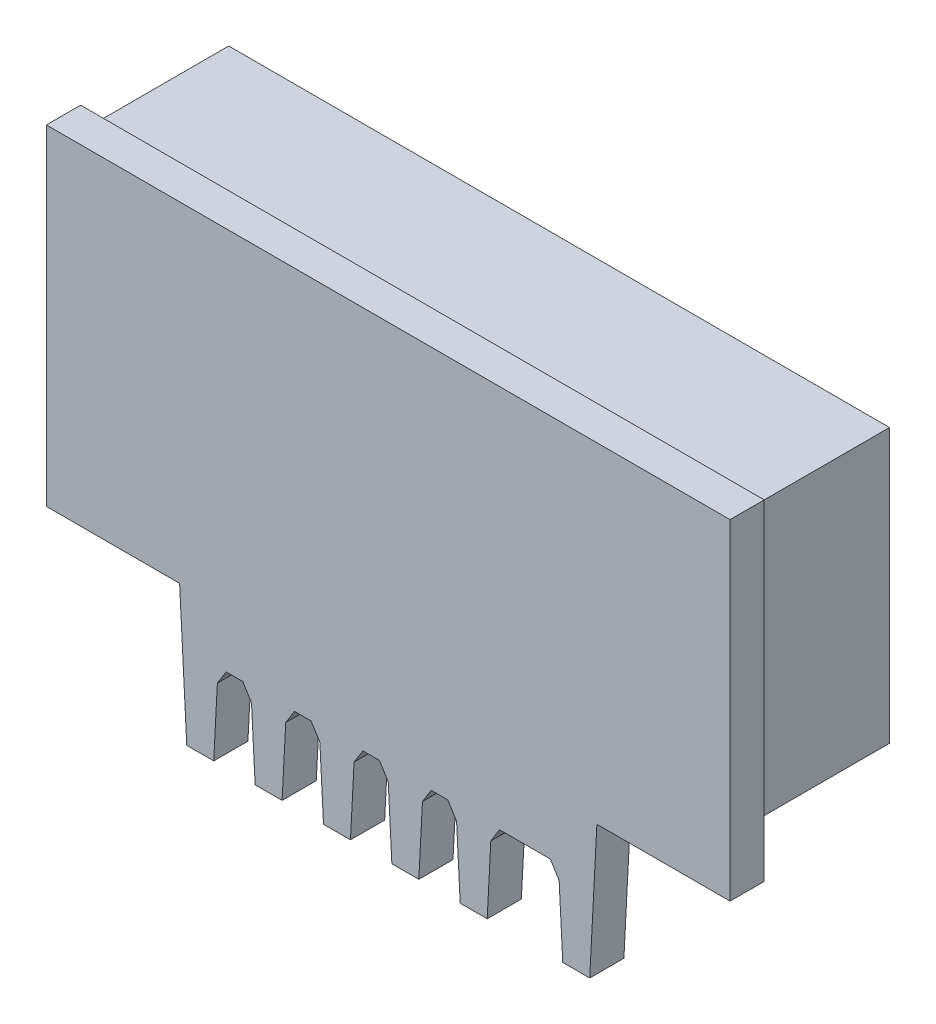
SolidWorks part; units mm, degrees
ref_plane "Front Plane" through (0, 0, 0) normal (0, 0, 1) x (1, 0, 0)
ref_plane "Top Plane" through (0, 0, 0) normal (0, 1, 0) x (1, 0, 0)
ref_plane "Right Plane" through (0, 0, 0) normal (1, 0, 0) x (0, 0, -1)
sketch "Sketch1" plane through (0, 0, 0) normal (0, 0, 1) x (1, 0, 0)
  line L0 (0, 0) -> (0, 20.5) construction
  line L1 (0, 20.5) -> (18.3124, 20.5) construction
  line L2 (18.3124, 20.5) -> (18.3124, 0) construction
  line L3 (18.3124, 0) -> (0, 0) construction
  line L4 (0, 3) -> (18.3124, 3) construction
  line L5 (0, 6) -> (18.3124, 6) construction
  line L6 (0.9062, 6) -> (0.9062, 0) construction
  line L7 (3.9062, 6) -> (3.9062, 0) construction
  line L8 (6.9062, 6) -> (6.9062, 0) construction
  line L9 (9.9062, 6) -> (9.9062, 0) construction
  line L10 (12.9062, 6) -> (12.9062, 0) construction
  line L11 (17.4062, 6) -> (17.4062, 0) construction
  line L12 (0.9062, 3) -> (3.9062, 3) construction
  line L13 (3.9062, 3) -> (6.9062, 3) construction
  line L14 (6.9062, 3) -> (9.9062, 3) construction
  line L15 (9.9062, 3) -> (12.9062, 3) construction
  line L16 (12.9062, 3) -> (17.4062, 3) construction
  line L17 (0.9062, 3) -> (0, 3) construction
  line L18 (17.4062, 3) -> (18.3124, 3) construction
  line L19 (2.4062, 3) -> (2.4062, 0) construction
  line L20 (5.4062, 3) -> (5.4062, 0) construction
  line L21 (8.4062, 3) -> (8.4062, 0) construction
  line L22 (11.4062, 3) -> (11.4062, 0) construction
  line L23 (15.1562, 3) -> (15.1562, 0) construction
  line L24 (14.4062, 3.75) -> (15.9062, 3.75) construction
  line L25 (0, 6) -> (0.3144, 0)
  line L26 (0.3144, 0) -> (1.4979, 0)
  line L27 (1.4979, 0) -> (1.6572, 3.0393)
  line L28 (3.1552, 3.0393) -> (3.3144, 0)
  line L29 (3.3144, 0) -> (4.4979, 0)
  line L30 (4.4979, 0) -> (4.6572, 3.0393)
  line L31 (6.1552, 3.0393) -> (6.3144, 0)
  line L32 (6.3144, 0) -> (7.4979, 0)
  line L33 (7.4979, 0) -> (7.6572, 3.0393)
  line L34 (9.1552, 3.0393) -> (9.3144, 0)
  line L35 (9.3144, 0) -> (10.4979, 0)
  line L36 (10.4979, 0) -> (10.6572, 3.0393)
  line L37 (12.1552, 3.0393) -> (12.3144, 0)
  line L38 (12.3144, 0) -> (13.4979, 0)
  line L39 (13.4979, 0) -> (13.6572, 3.0393)
  line L40 (16.6552, 3.0393) -> (16.8144, 0)
  line L41 (16.8144, 0) -> (17.9979, 0)
  line L42 (17.9979, 0) -> (18.3124, 6)
  line L44 (1.6572, 3.0393) -> (2.0426, 3.656)
  line L45 (0, 6) -> (-5.8438, 6)
  line L46 (-5.8438, 20.5) -> (24.1562, 20.5)
  line L47 (-5.8438, 6) -> (-5.8438, 20.5)
  line L48 (9.1562, 20.5) -> (9.1562, 6) construction
  line L49 (2.0426, 3.656) -> (2.7698, 3.656)
  line L50 (2.7698, 3.656) -> (3.1552, 3.0393)
  line L51 (4.6572, 3.0393) -> (5.0426, 3.656)
  line L52 (5.0426, 3.656) -> (5.7698, 3.656)
  line L53 (5.7698, 3.656) -> (6.1552, 3.0393)
  line L54 (7.6572, 3.0393) -> (8.0426, 3.656)
  line L55 (8.0426, 3.656) -> (8.7698, 3.656)
  line L56 (8.7698, 3.656) -> (9.1552, 3.0393)
  line L57 (10.6572, 3.0393) -> (11.0426, 3.656)
  line L58 (11.0426, 3.656) -> (11.7698, 3.656)
  line L59 (11.7698, 3.656) -> (12.1552, 3.0393)
  line L60 (13.6572, 3.0393) -> (14.0426, 3.656)
  line L61 (14.0426, 3.656) -> (16.2698, 3.656)
  line L62 (16.2698, 3.656) -> (16.6552, 3.0393)
  line L63 (18.3124, 6) -> (24.1562, 6)
  line L64 (24.1562, 6) -> (24.1562, 20.5)
  line L66 (23.6562, 20) -> (-5.3438, 20) construction
  line L67 (23.6562, 20) -> (23.6562, 8) construction
  line L68 (23.6562, 8) -> (-5.3438, 8) construction
  line L69 (-5.3438, 20) -> (-5.3438, 8) construction
  arc A0 (3.1552, 3.0393) -> (1.6572, 3.0393) centre (2.4062, 3) ccw construction
  arc A1 (6.1552, 3.0393) -> (4.6572, 3.0393) centre (5.4062, 3) ccw construction
  arc A2 (9.1552, 3.0393) -> (7.6572, 3.0393) centre (8.4062, 3) ccw construction
  arc A3 (12.1552, 3.0393) -> (10.6572, 3.0393) centre (11.4062, 3) ccw construction
  arc A4 (13.6572, 3.0393) -> (14.4062, 3.75) centre (14.4062, 3) cw construction
  arc A5 (16.6552, 3.0393) -> (15.9062, 3.75) centre (15.9062, 3) ccw construction
  dimension "D7" = 0.75
  dimension "D11" = 2
  dimension "D1" = 3
  dimension "D2" = 6
  dimension "D3" = 12
  dimension "D4" = 3
  dimension "D5" = 30
  dimension "D6" = 4.5
  dimension "D8" = 3
  dimension "D9" = 18.3124
  dimension "D10" = 20.5
  dimension "D12" = 14.5
  dimension "D13" = 0.5
  dimension "D14" = 0.5
  dimension "D15" = 29
extrude "Boss-Extrude1" add sketch "Sketch1" along normal blind 1.5
sketch "Sketch3" plane through (0, 0, 0) normal (0, 0, 1) x (1, 0, 0)
  line L0 (-0.4005, 6) -> (18.7129, 6)
  line L1 (18.7129, 3) -> (-0.4005, 3) construction
  line L2 (-0.4005, 0) -> (18.7129, 0) construction
  line L3 (-0.4005, -0.5) -> (18.7129, -0.5) construction
  line L4 (18.7129, -0.5) -> (18.7129, 6) construction
  line L5 (-0.4005, 6) -> (-0.4005, -0.5) construction
  line L6 (18.3124, 0) -> (0, 0) construction
  line L7 (0, 3) -> (18.3124, 3) construction
  line L8 (0, 6) -> (18.3124, 6) construction
  line L9 (0.3407, -0.5) -> (0, 6) construction
  line L10 (18.3124, 6) -> (17.9717, -0.5) construction
  line L11 (17.9979, 0) -> (18.3124, 6) construction
  line L12 (0, 6) -> (0.3144, 0) construction
  line L13 (5.4062, 6) -> (5.4062, -0.5) construction
  line L14 (3.9062, 6) -> (3.9062, -0.5) construction
  line L15 (5.4062, 3) -> (5.4062, 0) construction
  line L16 (3.1572, 3) -> (3.3407, -0.5) construction
  line L17 (2.7567, 3) -> (2.9401, -0.5)
  line L18 (3.1552, 3.0393) -> (3.3144, 0) construction
  line L19 (2.9401, -0.5) -> (4.8723, -0.5)
  line L20 (4.8723, -0.5) -> (5.0557, 3)
  line L21 (2.8484, 1.25) -> (3.2478, 1.2709) construction
  line L22 (5.9401, -0.5) -> (5.7567, 3)
  line L26 (7.8723, -0.5) -> (5.9401, -0.5)
  line L27 (8.0557, 3) -> (7.8723, -0.5)
  line L30 (2.4062, -0.5) -> (2.4062, 6) construction
  line L31 (2.4062, 3) -> (2.4062, 0) construction
  line L32 (8.4062, 6) -> (8.4062, -0.5) construction
  line L34 (11.4062, -0.5) -> (11.4062, 6) construction
  line L35 (15.1562, -0.5) -> (15.1562, 6) construction
  line L36 (8.4062, 3) -> (8.4062, 0) construction
  line L37 (11.4062, 3) -> (11.4062, 0) construction
  line L38 (15.1562, 3) -> (15.1562, 0) construction
  line L39 (10.8723, -0.5) -> (11.0557, 3)
  line L40 (8.9401, -0.5) -> (10.8723, -0.5)
  line L41 (8.7567, 3) -> (8.9401, -0.5)
  line L42 (11.9401, -0.5) -> (11.7567, 3)
  line L43 (13.8723, -0.5) -> (11.9401, -0.5)
  line L44 (14.0557, 3) -> (13.8723, -0.5)
  line L45 (16.4401, -0.5) -> (18.3723, -0.5)
  line L46 (16.2567, 3) -> (16.4401, -0.5)
  line L47 (18.3723, -0.5) -> (18.7129, 6)
  line L48 (1.8723, -0.5) -> (-0.0599, -0.5)
  line L49 (2.0557, 3) -> (1.8723, -0.5)
  line L50 (-0.0599, -0.5) -> (-0.4005, 6)
  line L51 (16.2567, 3) -> (14.0557, 3)
  line L52 (11.7567, 3) -> (11.0557, 3)
  line L53 (8.7567, 3) -> (8.0557, 3)
  line L54 (5.7567, 3) -> (5.0557, 3)
  line L55 (2.7567, 3) -> (2.0557, 3)
  dimension "D1" = 0.5
  dimension "D2" = 0.4
ref_plane "Plane1" through (3.9062, 0, 0) normal (1, 0, 0) x (0, 0, -1)
sketch "Sketch4" plane through (3.9062, 0, 0) normal (1, 0, 0) x (0, 0, -1)
  line L0 (0, 6) -> (0, -0.5) construction
  line L1 (0.6, 6) -> (-2.1, 6) construction
  line L2 (0.6, 6) -> (0.6, -0.5) construction
  line L3 (0.6, -0.5) -> (-2.1, -0.5) construction
  line L4 (-2.1, 6) -> (-2.1, -0.5) construction
  line L5 (-0.75, -0.5) -> (-0.75, 6) construction
  line L6 (-1.5, 6) -> (-1.5, -0.5) construction
  line L7 (0.6, 2.4005) -> (-2.1, 2.4005) construction
  line L8 (0.3, 6) -> (0.3, -0.5) construction
  line L9 (0.6, 2.4005) -> (3.846, 6) construction
  line L10 (2.2302, 6) -> (0.6, 4.1923) construction
  line L11 (0.6, 4.1923) -> (1.7139, 3.1878) construction
  line L12 (1.7139, 3.1878) -> (4.25, 6)
  line L13 (4.25, 6) -> (0.6, 6) construction
  line L14 (0.3, 1) -> (-1.8, 1) construction
  line L15 (-2.1, 0) -> (0.6, 0) construction
  line L16 (1.7139, 3.1878) -> (1.4912, 3.3887)
  line L17 (1.4912, 3.3887) -> (0.6, 2.4005)
  line L18 (-3.2139, 3.1878) -> (-5.75, 6)
  line L19 (-3.2139, 3.1878) -> (-2.9912, 3.3887)
  line L20 (-2.9912, 3.3887) -> (-2.1, 2.4005)
  line L21 (-2.1, 6) -> (-5.75, 6) construction
  line L22 (0.6, 3.0724) -> (3.2401, 6) construction
  arc A0 (0.4965, 2.2224) -> (0.6, -0.5) centre (4.2, 1) ccw
  arc A1 (0.6, 2.4005) -> (0.4965, 2.2224) centre (0.9713, 2.0656) ccw
  arc A2 (-2.1, 2.4005) -> (-1.9965, 2.2224) centre (-2.4713, 2.0656) cw
  arc A3 (-1.9965, 2.2224) -> (-2.1, -0.5) centre (-5.7, 1) cw
  dimension "D6" = 0.5
  dimension "D1" = 0.6
  dimension "D2" = 0.3
  dimension "D3" = 1.5
  dimension "D4" = 1
  dimension "D5" = 0.3
  dimension "D7" = 10
sketch "Sketch5" plane through (0, 0, 0) normal (1, 0, 0) x (0, 0, -1)
  line L0 (2.2302, 6) -> (0.6, 4.1923) construction
  line L1 (0.6, 4.1923) -> (1.7139, 3.1878) construction
  line L2 (1.7139, 3.1878) -> (4.25, 6) construction
  line L3 (2.2302, 6) -> (0.6, 4.1923) construction
  line L4 (0.6, 4.1923) -> (1.7139, 3.1878) construction
  line L5 (1.7139, 3.1878) -> (4.25, 6) construction
ref_plane "Plane2" through (0, 2.6105, -2.3541) normal (0, 0.7426, -0.6697) x (1, 0, 0)
sketch "Sketch6" plane through (0, 2.6105, -2.3541) normal (0, 0.7426, -0.6697) x (1, 0, 0)
  line L1 (3.9062, -2.362) -> (3.9062, -0.862) construction
  line L2 (3.9062, -2.362) -> (3.9062, -5.0612) construction
  line L3 (4.6562, -5.0612) -> (3.1562, -5.0612)
  line L4 (4.6562, -1.612) -> (3.1562, -1.612) construction
  line L5 (3.1562, -1.612) -> (3.1562, -5.0612)
  line L6 (4.6562, -1.612) -> (4.6562, -5.0612)
  line L10 (2.4062, -5.0612) -> (15.1562, -5.0612) construction
  line L11 (15.1562, -5.0612) -> (15.1562, -0.862) construction
  line L12 (15.1562, -0.862) -> (2.4062, -0.862) construction
  line L13 (2.4062, -0.862) -> (2.4062, -5.0612) construction
  line L14 (15.1562, 0.3349) -> (15.1562, -4.0182) construction
  line L15 (2.4062, 0.3349) -> (2.4062, -4.0182) construction
  line L16 (11.4062, -5.0612) -> (11.4062, -0.862) construction
  line L17 (8.4062, -5.0612) -> (8.4062, -0.862) construction
  line L18 (5.4062, -5.0612) -> (5.4062, -0.862) construction
  line L19 (5.4062, -4.0182) -> (5.4062, 0.3349) construction
  line L20 (8.4062, -4.0182) -> (8.4062, 0.3349) construction
  line L21 (11.4062, 0.3349) -> (11.4062, -4.0182) construction
  line L22 (0.1562, -1.612) -> (0.1562, -5.0612)
  line L23 (0.1562, -5.0612) -> (1.6562, -5.0612)
  line L24 (1.6562, -1.612) -> (1.6562, -5.0612)
  line L25 (7.6562, -1.612) -> (7.6562, -5.0612)
  line L26 (6.1562, -5.0612) -> (7.6562, -5.0612)
  line L27 (6.1562, -1.612) -> (6.1562, -5.0612)
  line L28 (10.6562, -1.612) -> (10.6562, -5.0612)
  line L29 (10.6562, -5.0612) -> (9.1562, -5.0612)
  line L30 (9.1562, -1.612) -> (9.1562, -5.0612)
  line L31 (13.6562, -1.612) -> (13.6562, -5.0612)
  line L32 (12.1562, -5.0612) -> (13.6562, -5.0612)
  line L33 (12.1562, -1.612) -> (12.1562, -5.0612)
  line L34 (18.1562, -1.612) -> (18.1562, -5.0612)
  line L35 (18.1562, -5.0612) -> (16.6562, -5.0612)
  line L36 (16.6562, -1.612) -> (16.6562, -5.0612)
  circle A0 centre (3.9062, -1.612) radius 0.75 construction
  arc A1 (4.6562, -1.612) -> (3.1562, -1.612) centre (3.9062, -1.612) ccw
  arc A2 (0.1562, -1.612) -> (1.6562, -1.612) centre (0.9062, -1.612) cw
  arc A3 (6.1562, -1.612) -> (7.6562, -1.612) centre (6.9062, -1.612) cw
  arc A4 (10.6562, -1.612) -> (9.1562, -1.612) centre (9.9062, -1.612) ccw
  arc A5 (12.1562, -1.612) -> (13.6562, -1.612) centre (12.9062, -1.612) cw
  arc A6 (18.1562, -1.612) -> (16.6562, -1.612) centre (17.4062, -1.612) ccw
ref_plane "Plane3" through (0, 1.6223, -1.463) normal (0, 0.7426, -0.6697) x (1, 0, 0)
sketch "Sketch7" plane through (0, 1.6223, -1.463) normal (0, 0.7426, -0.6697) x (1, 0, 0)
  line L0 (3.1562, -1.612) -> (3.1562, -5.0612) construction
  line L1 (4.6562, -5.0612) -> (3.1562, -5.0612) construction
  line L2 (4.6562, -1.612) -> (4.6562, -5.0612) construction
  line L3 (3.1562, -1.612) -> (3.1562, -5.0612) construction
  line L4 (4.6562, -5.0612) -> (3.1562, -5.0612) construction
  line L5 (4.6562, -1.612) -> (4.6562, -5.0612) construction
  line L6 (3.9062, -0.862) -> (3.9062, -5.0612) construction
  line L7 (4.6562, -1.612) -> (3.1562, -1.612) construction
  line L8 (4.6562, -2.362) -> (3.1562, -2.362) construction
  line L9 (3.4562, -1.612) -> (3.4562, -2.362)
  line L10 (3.4562, -2.362) -> (4.3562, -2.362)
  line L11 (4.3562, -2.362) -> (4.3562, -1.612)
  line L12 (2.4062, -0.862) -> (2.4062, -5.0612) construction
  line L13 (2.4062, -5.0612) -> (15.1562, -5.0612) construction
  line L14 (15.1562, -0.862) -> (2.4062, -0.862) construction
  line L15 (5.4062, -5.0612) -> (5.4062, -0.862) construction
  line L16 (8.4062, -5.0612) -> (8.4062, -0.862) construction
  line L17 (11.4062, -5.0612) -> (11.4062, -0.862) construction
  line L18 (15.1562, -5.0612) -> (15.1562, -0.862) construction
  line L19 (2.4062, -0.862) -> (2.4062, -5.0612) construction
  line L20 (2.4062, -5.0612) -> (15.1562, -5.0612) construction
  line L21 (15.1562, -0.862) -> (2.4062, -0.862) construction
  line L22 (5.4062, -5.0612) -> (5.4062, -0.862) construction
  line L23 (8.4062, -5.0612) -> (8.4062, -0.862) construction
  line L24 (11.4062, -5.0612) -> (11.4062, -0.862) construction
  line L25 (15.1562, -5.0612) -> (15.1562, -0.862) construction
  line L26 (0.4562, -2.362) -> (0.4562, -1.612)
  line L27 (1.3562, -2.362) -> (0.4562, -2.362)
  line L28 (1.3562, -1.612) -> (1.3562, -2.362)
  line L29 (7.3562, -2.362) -> (6.4562, -2.362)
  line L30 (7.3562, -1.612) -> (7.3562, -2.362)
  line L31 (6.4562, -2.362) -> (6.4562, -1.612)
  line L32 (9.4562, -1.612) -> (9.4562, -2.362)
  line L33 (10.3562, -2.362) -> (10.3562, -1.612)
  line L34 (9.4562, -2.362) -> (10.3562, -2.362)
  line L35 (13.3562, -1.612) -> (13.3562, -2.362)
  line L36 (12.4562, -2.362) -> (12.4562, -1.612)
  line L37 (13.3562, -2.362) -> (12.4562, -2.362)
  line L38 (16.9562, -1.612) -> (16.9562, -2.362)
  line L39 (17.8562, -2.362) -> (17.8562, -1.612)
  line L40 (16.9562, -2.362) -> (17.8562, -2.362)
  arc A0 (4.6562, -1.612) -> (3.1562, -1.612) centre (3.9062, -1.612) ccw construction
  arc A1 (4.6562, -1.612) -> (3.1562, -1.612) centre (3.9062, -1.612) ccw construction
  circle A2 centre (3.9062, -1.612) radius 0.45 construction
  arc A3 (4.3562, -1.612) -> (3.4562, -1.612) centre (3.9062, -1.612) ccw
  arc A4 (0.4562, -1.612) -> (1.3562, -1.612) centre (0.9062, -1.612) cw
  arc A5 (6.4562, -1.612) -> (7.3562, -1.612) centre (6.9062, -1.612) cw
  arc A6 (10.3562, -1.612) -> (9.4562, -1.612) centre (9.9062, -1.612) ccw
  arc A7 (12.4562, -1.612) -> (13.3562, -1.612) centre (12.9062, -1.612) cw
  arc A8 (17.8562, -1.612) -> (16.9562, -1.612) centre (17.4062, -1.612) ccw
ref_plane "bisect" through (0, 0, 0.75) normal (0, 0, 1) x (1, 0, 0)
ref_plane "insert_surface" through (0, 6, 0) normal (0, 1, 0) x (1, 0, 0)
sketch "Sketch8" plane through (0, 6, 0) normal (0, 1, 0) x (1, 0, 0)
  line L0 (18.7129, -0.75) -> (-0.4005, -0.75) construction
  line L1 (-0.4005, 0.6) -> (18.7129, 0.6)
  line L2 (-0.4005, 0.6) -> (-0.4005, -2.1)
  line L3 (-0.4005, -2.1) -> (18.7129, -2.1)
  line L4 (18.7129, 0.6) -> (18.7129, -2.1)
  line L5 (9.1562, 0.6) -> (9.1562, -2.1) construction
  line L6 (0, 0) -> (18.3124, 0) construction
  line L7 (0, 0) -> (0, -1.5) construction
  line L8 (0, -1.5) -> (18.3124, -1.5) construction
  line L9 (18.3124, 0) -> (18.3124, -1.5) construction
  line L10 (18.7129, 0.3) -> (-0.4005, 0.3) construction
  line L11 (18.7129, -1.8) -> (-0.4005, -1.8) construction
sketch "Sketch9" plane through (0, 0, 0) normal (0, 0, 1) x (1, 0, 0)
  line L0 (18.3723, -0.5) -> (18.7129, 6) construction
  line L1 (-0.4005, 6) -> (18.7129, 6) construction
  line L2 (-0.0599, -0.5) -> (-0.4005, 6) construction
  line L3 (1.8723, -0.5) -> (-0.0599, -0.5) construction
  line L4 (2.0557, 3) -> (1.8723, -0.5) construction
  line L5 (2.7567, 3) -> (2.0557, 3) construction
  line L6 (2.7567, 3) -> (2.9401, -0.5) construction
  line L7 (2.9401, -0.5) -> (4.8723, -0.5) construction
  line L8 (4.8723, -0.5) -> (5.0557, 3) construction
  line L9 (5.7567, 3) -> (5.0557, 3) construction
  line L10 (5.9401, -0.5) -> (5.7567, 3) construction
  line L11 (7.8723, -0.5) -> (5.9401, -0.5) construction
  line L12 (8.0557, 3) -> (7.8723, -0.5) construction
  line L13 (8.7567, 3) -> (8.0557, 3) construction
  line L14 (8.7567, 3) -> (8.9401, -0.5) construction
  line L15 (8.9401, -0.5) -> (10.8723, -0.5) construction
  line L16 (10.8723, -0.5) -> (11.0557, 3) construction
  line L17 (11.7567, 3) -> (11.0557, 3) construction
  line L18 (11.9401, -0.5) -> (11.7567, 3) construction
  line L19 (13.8723, -0.5) -> (11.9401, -0.5) construction
  line L20 (14.0557, 3) -> (13.8723, -0.5) construction
  line L21 (16.2567, 3) -> (14.0557, 3) construction
  line L22 (16.2567, 3) -> (16.4401, -0.5) construction
  line L23 (16.4401, -0.5) -> (18.3723, -0.5) construction
  line L24 (18.3723, -0.5) -> (18.7129, 6)
  line L25 (-0.4005, 6) -> (18.7129, 6) construction
  line L26 (-0.0599, -0.5) -> (-0.4005, 6)
  line L27 (1.8723, -0.5) -> (-0.0599, -0.5)
  line L28 (2.0557, 3) -> (1.8723, -0.5)
  line L29 (2.7567, 3) -> (2.0557, 3) construction
  line L30 (2.7567, 3) -> (2.9401, -0.5)
  line L31 (2.9401, -0.5) -> (4.8723, -0.5)
  line L32 (4.8723, -0.5) -> (5.0557, 3)
  line L33 (5.7567, 3) -> (5.0557, 3) construction
  line L34 (5.9401, -0.5) -> (5.7567, 3)
  line L35 (7.8723, -0.5) -> (5.9401, -0.5)
  line L36 (8.0557, 3) -> (7.8723, -0.5)
  line L37 (8.7567, 3) -> (8.0557, 3) construction
  line L38 (8.7567, 3) -> (8.9401, -0.5)
  line L39 (8.9401, -0.5) -> (10.8723, -0.5)
  line L40 (10.8723, -0.5) -> (11.0557, 3)
  line L41 (11.7567, 3) -> (11.0557, 3) construction
  line L42 (11.9401, -0.5) -> (11.7567, 3)
  line L43 (13.8723, -0.5) -> (11.9401, -0.5)
  line L44 (14.0557, 3) -> (13.8723, -0.5)
  line L45 (16.2567, 3) -> (14.0557, 3) construction
  line L46 (16.2567, 3) -> (16.4401, -0.5)
  line L47 (16.4401, -0.5) -> (18.3723, -0.5)
  line L48 (16.2567, 3) -> (16.2567, 6)
  line L49 (14.0557, 3) -> (14.0557, 6)
  line L50 (11.7567, 3) -> (11.7567, 6)
  line L51 (18.7129, 6) -> (-0.4005, 6) construction
  line L52 (11.0557, 3) -> (11.0557, 6)
  line L53 (-0.4005, 6) -> (18.7129, 6) construction
  line L54 (8.7567, 3) -> (8.7567, 6)
  line L55 (8.0557, 3) -> (8.0557, 6)
  line L58 (5.7567, 3) -> (5.7567, 6)
  line L60 (5.0557, 3) -> (5.0557, 6)
  line L62 (15.1562, -0.5) -> (15.1562, 6) construction
  line L63 (15.1562, -0.5) -> (15.1562, 6) construction
  line L64 (2.7567, 3) -> (2.7567, 6)
  line L65 (2.0557, 3) -> (2.0557, 6)
  line L67 (18.7129, 6) -> (16.2567, 6)
  line L68 (14.0557, 6) -> (11.7567, 6)
  line L69 (11.0557, 6) -> (8.7567, 6)
  line L70 (8.0557, 6) -> (5.7567, 6)
  line L71 (5.0557, 6) -> (2.7567, 6)
  line L72 (2.0557, 6) -> (-0.4005, 6)
sketch "Sketch11" plane through (0, 6, 0) normal (0, 1, 0) x (1, 0, 0)
  line L0 (9.1562, -0.75) -> (9.1562, -5.75) construction
  line L1 (-0.8438, 4.25) -> (19.1562, 4.25)
  line L2 (-0.8438, 4.25) -> (-0.8438, -5.75)
  line L3 (-0.8438, -5.75) -> (19.1562, -5.75)
  line L4 (19.1562, 4.25) -> (19.1562, -5.75)
  line L5 (9.1562, -0.75) -> (9.1562, 4.25) construction
  line L6 (9.1562, -0.75) -> (19.1562, -0.75) construction
  line L7 (9.1562, -0.75) -> (-0.8438, -0.75) construction
  line L8 (-10.5124, -0.75) -> (10.5124, -0.75) construction
  dimension "D1" = 10
  dimension "D2" = 20
sketch "Sketch12" plane through (0, 0, 0) normal (0, 0, 1) x (1, 0, 0)
  line L0 (-5.3438, 20) -> (-5.3438, 8)
  line L1 (-5.3438, 8) -> (23.6562, 8)
  line L2 (23.6562, 8) -> (23.6562, 20)
  line L3 (23.6562, 20) -> (-5.3438, 20)
  line L4 (23.6562, 8) -> (-5.3438, 8) construction
  line L8 (23.6562, 20) -> (-5.3438, 20) construction
  line L9 (-5.3438, 20) -> (-5.3438, 8) construction
  line L10 (23.6562, 20) -> (23.6562, 8) construction
extrude "Boss-Extrude2" add sketch "Sketch12" against normal blind 6
ref_plane "right_center" through (9.1562, 0, 0) normal (1, 0, 0) x (0, 0, -1)
